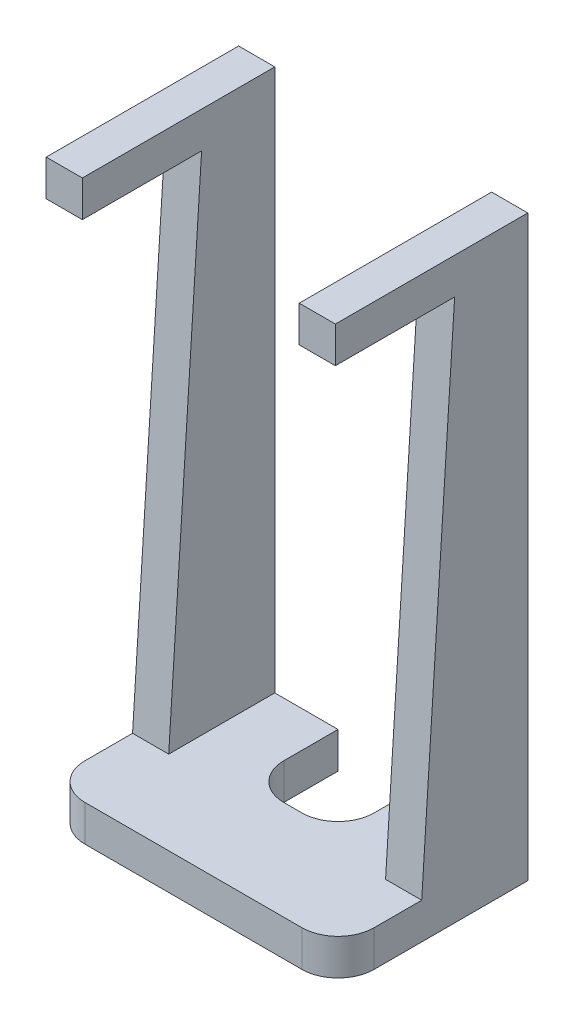
SolidWorks part; units mm, degrees
ref_plane "Front Plane" through (0, 0, 0) normal (0, 0, 1) x (1, 0, 0)
ref_plane "Top Plane" through (0, 0, 0) normal (0, 1, 0) x (1, 0, 0)
ref_plane "Right Plane" through (0, 0, 0) normal (1, 0, 0) x (0, 0, -1)
sketch "Sketch2" plane through (0, 0, 0) normal (0, 1, 0) x (1, 0, 0)
  line L1 (-8, 5.25) -> (8, 5.25)
  line L2 (-8, 5.25) -> (-8, -5.25)
  line L3 (-8, -5.25) -> (8, -5.25)
  line L4 (8, 5.25) -> (8, -5.25)
  line L5 (-8, 5.25) -> (8, -5.25) construction
  line L6 (-8, -5.25) -> (8, 5.25) construction
  point P0 (0, 0)
  dimension "D1" = 10.5
  dimension "D2" = 16
extrude "base" add sketch "Sketch2" along normal blind 2
sketch "Sketch3" plane through (8, 0, 0) normal (1, 0, 0) x (0, 0, -1)
  line L0 (5.25, 0) -> (5.25, 32)
  line L1 (5.25, 32) -> (-5.3966, 32)
  line L2 (-5.3966, 32) -> (-5.3966, 30)
  line L3 (1.202, 30) -> (-0.75, 0)
  line L4 (-5.25, 0) -> (5.25, 0) construction
  line L5 (-5.3966, 30) -> (1.202, 30)
  line L6 (-0.75, 0) -> (5.25, 0)
  point P3 (-1.9132, 0)
  point P9 (3.25, 33)
  point P10 (-8.2681, 32)
  point P11 (-0.549, 30)
  point P13 (-7.3966, 32)
  point P14 (-0.798, 30)
  dimension "D1" = 32
  dimension "D2" = 10.6466
  dimension "D3" = 2
  dimension "D4" = 30
  dimension "D5" = 6
  dimension "D6" = 6.5986
extrude "arm" add sketch "Sketch3" against normal blind 2
pattern_linear "LPattern1" count 2 spacing 14 along (-1, 0, 0) of "arm"
sketch "Sketch4" plane through (0, 0, 0) normal (0, -1, 0) x (1, 0, 0)
  line L0 (0, 0) -> (0, -5.25) construction
  line L1 (8, -5.25) -> (-8, -5.25) construction
  line L3 (-2.5, -0.25) -> (2.5, -0.25)
  line L4 (-2.5, -0.25) -> (-2.5, -5.25)
  line L5 (-2.5, -5.25) -> (2.5, -5.25)
  line L6 (2.5, -0.25) -> (2.5, -5.25)
  line L7 (-2.5, -0.25) -> (2.5, -5.25) construction
  line L8 (-2.5, -5.25) -> (2.5, -0.25) construction
  point P5 (0, -2.75)
  dimension "D1" = 5
  dimension "D2" = 5
extrude "Cut-Extrude1" cut sketch "Sketch4" against normal through all
fillet "Fillet1" radius 2 4 edges at (2.5, 1, -0.25) (-2.5, 1, -0.25) (8, 1, 5.25) (-8, 1, 5.25)
